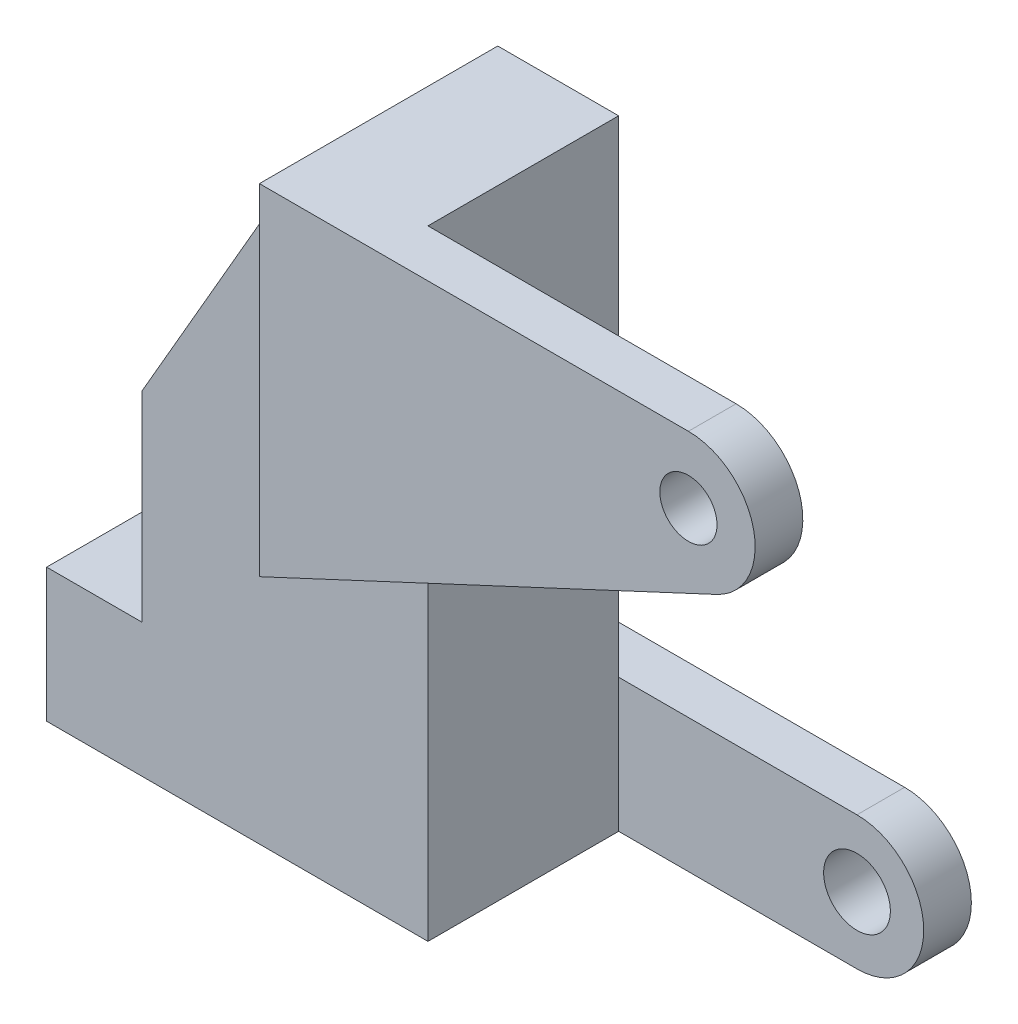
SolidWorks part; units mm, degrees
ref_plane "Front Plane" through (0, 0, 0) normal (0, 0, 1) x (1, 0, 0)
ref_plane "Top Plane" through (0, 0, 0) normal (0, 1, 0) x (1, 0, 0)
ref_plane "Right Plane" through (0, 0, 0) normal (1, 0, 0) x (0, 0, -1)
sketch "Sketch1" plane through (0, 0, 0) normal (0, 0, 1) x (1, 0, 0)
  line L0 (0, 0) -> (40, 0)
  line L1 (0, 0) -> (0, 14)
  line L2 (0, 14) -> (10, 14)
  line L3 (10, 14) -> (10, 35)
  line L4 (10, 35) -> (27.3205, 65)
  line L5 (40, 0) -> (40, 65)
  line L6 (40, 65) -> (27.3205, 65)
  dimension "D1" = 14
  dimension "D2" = 40
  dimension "D3" = 21
  dimension "D4" = 30
  dimension "D5" = 65
extrude "Boss-Extrude1" add sketch "Sketch1" along normal blind 20
sketch "Sketch2" plane through (0, 0, 20) normal (0, 0, 1) x (1, 0, 0)
  line L0 (27.3205, 65) -> (72.3205, 65)
  line L1 (75.2788, 51.6558) -> (27.3205, 29.2925)
  line L2 (40, 0) -> (40, 65) construction
  line L3 (27.3205, 65) -> (27.3205, 29.2925)
  circle A0 centre (72.3205, 58) radius 7
  circle A1 centre (72.3205, 58) radius 3
  point P10 (0, 0)
  point P12 (0, 0)
  point P13 (27.3205, 29.2991)
  point P14 (27.3345, 29.8517)
  line M7 (40, 0) -> (40, 65)
  line M8 (40, 65) -> (27.3205, 65)
  dimension "D1" = 65
  dimension "D2" = 14
  dimension "D3" = 6
  dimension "D4" = 45
extrude "Boss-Extrude2" add sketch "Sketch2" along normal blind 5 contours L3 L1 M8 M7 | A0 L0 L1 M7 | A0 A1
sketch "Sketch3" plane through (0, 0, 0) normal (0, 0, -1) x (-1, 0, 0)
  line L0 (-10, 14) -> (-65, 14)
  line L1 (-65, 0) -> (-40, 0)
  line L2 (-10, 14) -> (-10, 0)
  line L3 (0, 0) -> (-40, 0) construction
  circle A0 centre (-65, 7) radius 7
  circle A1 centre (-65, 7) radius 3.5
  line M7 (-40, 65) -> (-40, 0)
  line M8 (-40, 0) -> (0, 0)
  dimension "D1" = 55
extrude "Boss-Extrude3" add sketch "Sketch3" along normal blind 5 contours A0 L1 L0 M7 | L2 L0 M7 M8 | A0 A1
